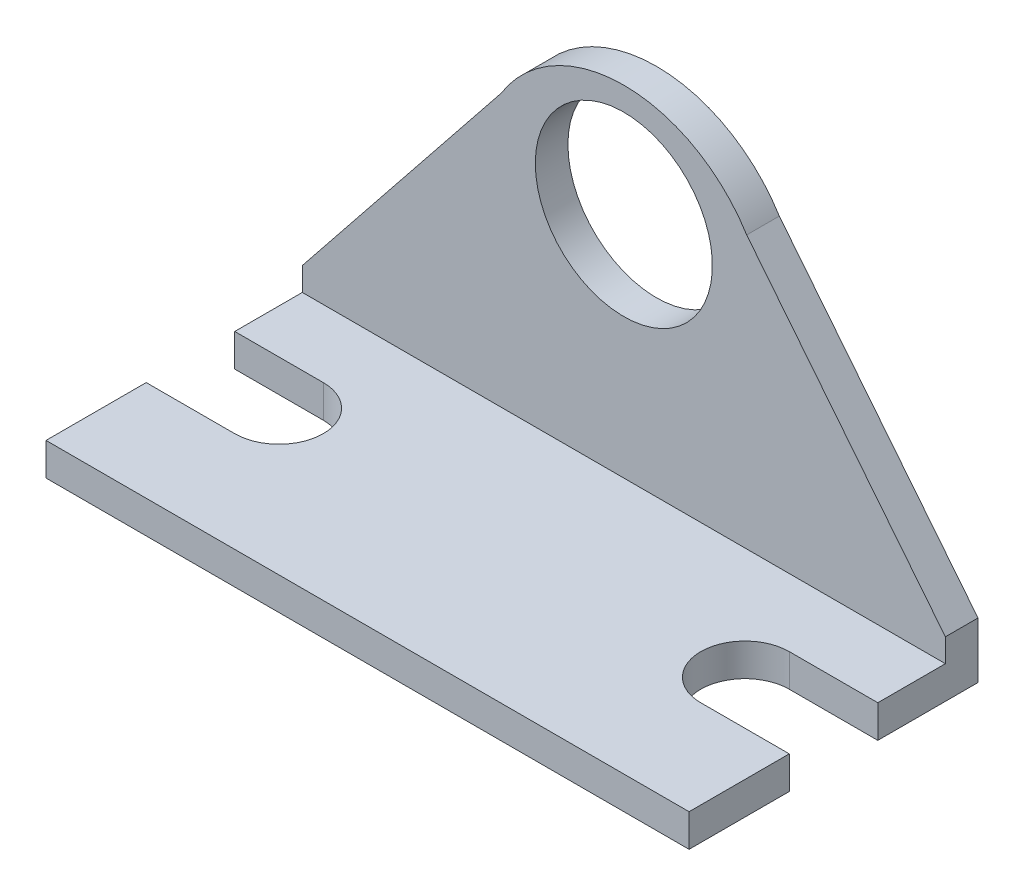
SolidWorks part; units mm, degrees
ref_plane "Front Plane" through (0, 0, 0) normal (0, 0, 1) x (1, 0, 0)
ref_plane "Top Plane" through (0, 0, 0) normal (0, 1, 0) x (1, 0, 0)
ref_plane "Right Plane" through (0, 0, 0) normal (1, 0, 0) x (0, 0, -1)
sketch "Sketch1" plane through (0, 0, 0) normal (0, 1, 0) x (1, 0, 0)
  line L0 (-12.7, 2.413) -> (-17.526, 2.413)
  line L1 (-17.526, 7.874) -> (17.526, 7.874)
  line L2 (-12.7, -2.413) -> (-17.526, -2.413)
  line L3 (0, 27.3208) -> (0, -7.466) construction
  line L4 (-17.526, 2.413) -> (-17.526, 7.874)
  line L5 (-17.526, -2.413) -> (-17.526, -7.874)
  line L6 (-17.526, -7.874) -> (17.526, -7.874)
  line L7 (17.526, -2.413) -> (17.526, -7.874)
  line L8 (17.526, 2.413) -> (17.526, 7.874)
  line L9 (12.7, -2.413) -> (17.526, -2.413)
  line L10 (12.7, 2.413) -> (17.526, 2.413)
  circle A0 centre (-12.7, 0) radius 2.413
  circle A1 centre (12.7, 0) radius 2.413
  point P16 (0, -7.874)
  point P20 (0, 7.874)
  dimension "D1" = 4.826
  dimension "D2" = 15.748
  dimension "D3" = 12.7
  dimension "D4" = 4.826
extrude "Boss-Extrude1" add sketch "Sketch1" along normal blind 1.778 contours L3 L1 L4 L0 A0 L2 L5 L6 | L1 L3 L6 L7 L9 A1 L10 L8
sketch "Sketch3" plane through (0, 0, -7.874) normal (0, 0, -1) x (-1, 0, 0)
  line L0 (17.526, 3.048) -> (17.526, 1.778)
  line L1 (17.526, 3.048) -> (6.6898, 16.5977)
  line L2 (-17.526, 1.778) -> (-17.526, 3.048)
  line L3 (-17.526, 3.048) -> (-6.6965, 16.6031)
  line L4 (17.526, 0) -> (-17.526, 0) construction
  circle A0 centre (0, 14.224) radius 4.826
  arc A1 (6.6898, 16.5977) -> (-6.6965, 16.6031) centre (-0.0051, 12.4529) ccw
  line M5 (17.526, 1.778) -> (-17.526, 1.778)
  dimension "D1" = 9.652
  dimension "D2" = 3.048
  dimension "D3" = 17.526
  dimension "D4" = 14.224
extrude "Boss-Extrude2" add sketch "Sketch3" against normal blind 1.778 contours L1 A1 L3 L2 L0 A0 M5
